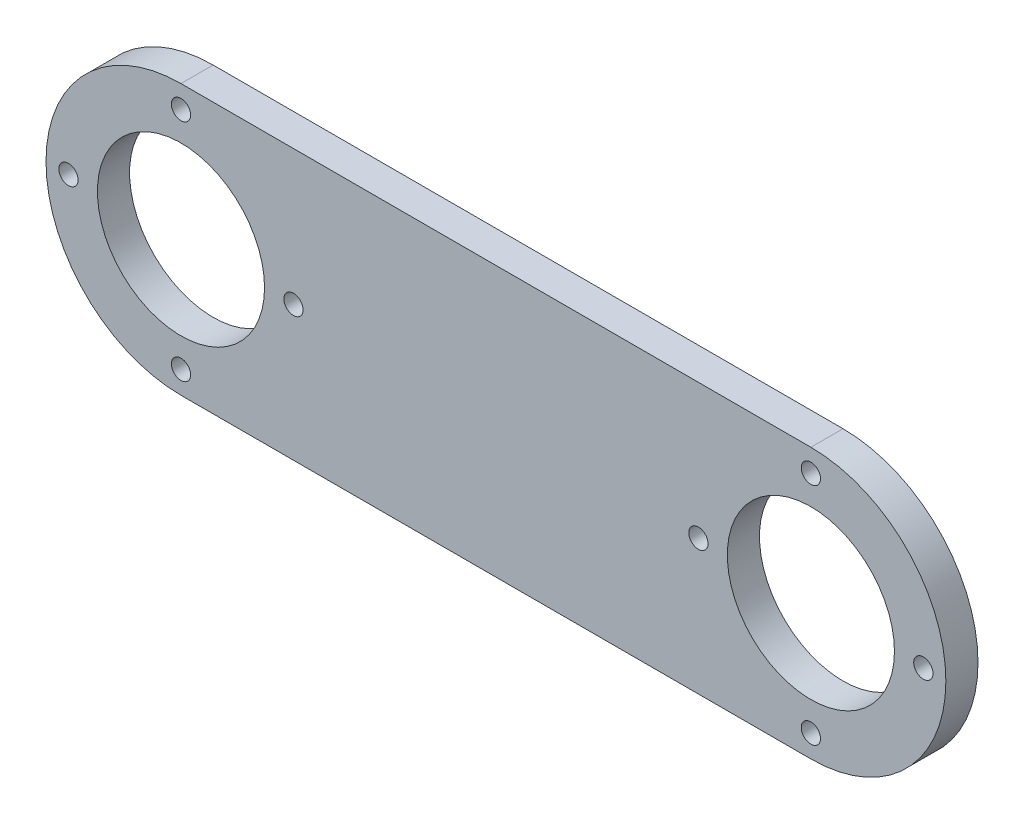
SolidWorks part; units mm, degrees
material "Thornel Mat VMA"
ref_plane "Front Plane" through (0, 0, 0) normal (0, 0, 1) x (1, 0, 0)
ref_plane "Top Plane" through (0, 0, 0) normal (0, 1, 0) x (1, 0, 0)
ref_plane "Right Plane" through (0, 0, 0) normal (1, 0, 0) x (0, 0, -1)
sketch "Sketch1" plane through (0, 0, 0) normal (0, 0, 1) x (1, 0, 0)
  line L0 (-49, 26) -> (49, 26)
  line L1 (-49, -16) -> (49, -16)
  arc A1 (-49, 26) -> (-49, -16) centre (-49, 5) ccw
  arc A3 (49, -16) -> (49, 26) centre (49, 5) ccw
  arc A4 (49, -14) -> (49, -11) centre (49, -12.5) ccw construction
  arc A5 (66.5, 3.5) -> (66.5, 6.5) centre (66.5, 5) ccw construction
  arc A6 (31.5, 3.5) -> (31.5, 6.5) centre (31.5, 5) ccw construction
  arc A7 (49, 21) -> (49, 24) centre (49, 22.5) ccw construction
  arc A8 (-49, -14) -> (-49, -11) centre (-49, -12.5) ccw construction
  arc A9 (-31.5, 3.5) -> (-31.5, 6.5) centre (-31.5, 5) ccw construction
  arc A10 (-66.5, 3.5) -> (-66.5, 6.5) centre (-66.5, 5) ccw construction
  arc A11 (-49, 24) -> (-49, 21) centre (-49, 22.5) ccw construction
  circle A12 centre (49, -12.5) radius 1.5
  circle A13 centre (66.5, 5) radius 1.5
  circle A14 centre (31.5, 5) radius 1.5
  circle A15 centre (49, 22.5) radius 1.5
  circle A16 centre (-49, -12.5) radius 1.5
  circle A17 centre (-31.5, 5) radius 1.5
  circle A18 centre (-66.5, 5) radius 1.5
  circle A19 centre (-49, 22.5) radius 1.5
  arc A20 (-49, -8) -> (-49, 18) centre (-49, 5) ccw construction
  circle A21 centre (-49, 5) radius 13
  arc A22 (49, -8) -> (49, 18) centre (49, 5) ccw construction
  circle A23 centre (49, 5) radius 13
  dimension "D1" = 21
extrude "Boss-Extrude1" add sketch "Sketch1" along normal blind 5
